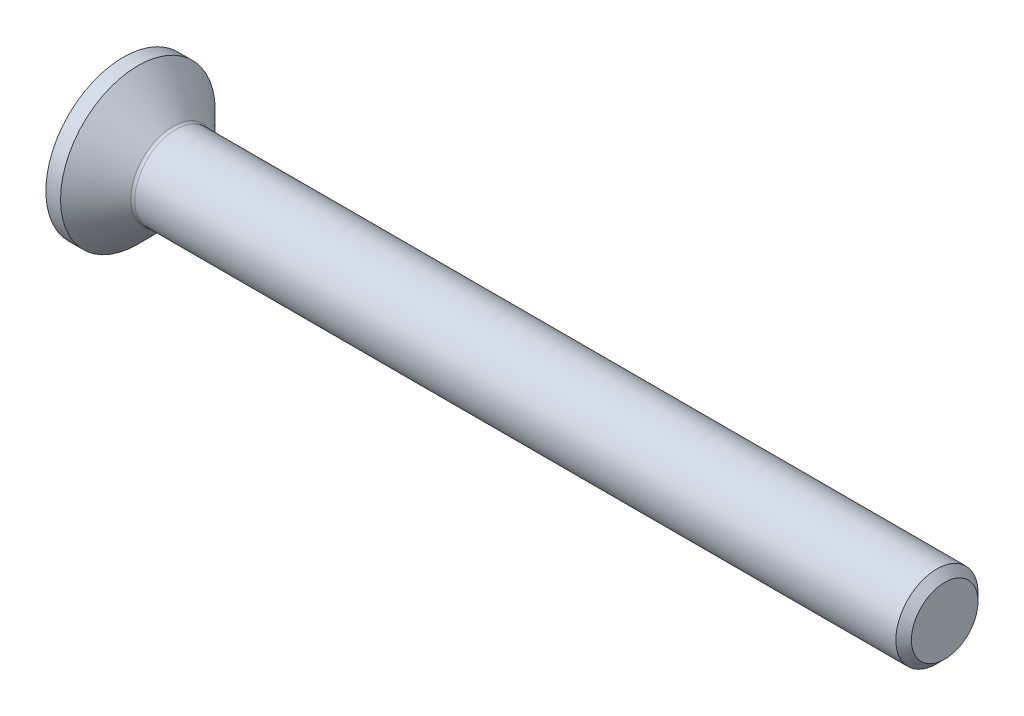
SolidWorks part; units mm, degrees
ref_plane "Front" through (0, 0, 0) normal (0, 0, 1) x (1, 0, 0)
ref_plane "Top" through (0, 0, 0) normal (0, 1, 0) x (1, 0, 0)
ref_plane "Right" through (0, 0, 0) normal (1, 0, 0) x (0, 0, -1)
sketch "Sketch1" plane through (0, 0, 0) normal (0, 0, 1) x (1, 0, 0)
  line L0 (0, 0) -> (0, 4.48)
  line L1 (0, 4.48) -> (2.48, 2)
  line L2 (2.48, 2) -> (40, 2)
  line L3 (40, 2) -> (40, 0)
  line L4 (40, 0) -> (0, 0)
  line L5 (-0.5871, 0) -> (5.4927, 0) construction
  dimension "l" = 40
  dimension "k" = 2.48
  dimension "d" = 4
  dimension "D1" = 45
revolve "Base" add sketch "Sketch1" angle 360 about L5
cosmetic thread "ThreadCosmetic1" parameters "b"=20, "D2"=3.242
sketch "Sketch2" plane through (0, 0, 0) normal (1, 0, 0) x (0, 0, -1)
  line L1 (1.4434, 0) -> (0.7217, 1.25)
  line L2 (0.7217, 1.25) -> (-0.7217, 1.25)
  line L3 (-0.7217, 1.25) -> (-1.4434, 0)
  line L4 (-1.4434, 0) -> (-0.7217, -1.25)
  line L5 (-0.7217, -1.25) -> (0.7217, -1.25)
  line L6 (0.7217, -1.25) -> (1.4434, 0)
  circle A0 centre (0, 0) radius 1.25 construction
  dimension "s" = 2.5
extrude "HexagonSocket" cut sketch "Sketch2" along normal blind 1.5
sketch "Sketch3" plane through (0, 0, 0) normal (0, 0, 1) x (1, 0, 0)
  line L0 (-0.4391, 0) -> (4.425, 0) construction
  line L1 (1.5, 0) -> (1.5, -1.25) construction
  line L2 (1.5, 1.25) -> (2.2217, 0)
  line L3 (2.2217, 0) -> (1.5, -1.25) construction
  line L4 (1.5, 1.25) -> (1.5, 0)
  line L5 (1.5, 0) -> (2.2217, 0)
  line L7 (1.5, 1.25) -> (1.5, 0) construction
  dimension "D1" = 120
revolve "Cut-Revolve1" cut sketch "Sketch3" angle 360 about L0
fillet "HeadFillet" radius 0.2 1 edges at (2.48, 0, 2)
chamfer "Chamfer" distance 0.379 angle 45 1 edges at (40, 0, 2)
sketch "Sketch4" plane through (0, 0, 0) normal (0, 1, 0) x (1, 0, 0)
  line L0 (11.8531, 0) -> (-2.694, 0) construction
  line L1 (-2, 8.765) -> (3, 8.765)
  line L2 (-2, 8.765) -> (-2, 3.765)
  line L3 (-2, 3.765) -> (3, 3.765)
  line L4 (3, 8.765) -> (3, 3.765)
  line L5 (0, 4.48) -> (0, -4.48) construction
  dimension "dk" = 7.53
  dimension "D2" = 2
  dimension "D3" = 5
  dimension "D4" = 5
revolve "Cut-Revolve2" cut sketch "Sketch4" angle 360 about L0
sketch "Sketch5" plane through (0, 0, 0) normal (0, 0, 1) x (1, 0, 0)
  line L0 (39.621, 1.6718) -> (39.8105, 2)
  line L1 (39.8105, 2) -> (39.8105, 2.379)
  line L2 (39.8105, 2.379) -> (39.4315, 2.379)
  line L3 (39.4315, 2.379) -> (39.4315, 2)
  line L4 (39.4315, 2) -> (39.621, 1.6718)
  line L5 (0, 0) -> (10.6885, 0) construction
  line L6 (39.621, 2) -> (39.621, -2) construction
  dimension "D1" = 4
  dimension "D2" = 0.379
revolve "Cut-Revolve10" [suppressed] cut sketch "Sketch5" angle 360 about L5
pattern_linear "LPattern10" [suppressed] count 44 spacing 0.4548 along (1, 0, 0)
equation "\"D1@Chamfer\" = (  \"d@Sketch1\" - \"D2@ThreadCosmetic1\" )  / 2"
equation "\"D1@Sketch5\" = \"d@Sketch1\""
equation "\"D2@Sketch5\" =  ( \"d@Sketch1\" - \"D2@ThreadCosmetic1\" )  / 2"
equation "\"D3@LPattern10\" = \"D2@Sketch5\" * 1.2"
equation "\"D1@LPattern10\" = \"b@ThreadCosmetic1\" / \"D3@LPattern10\""
